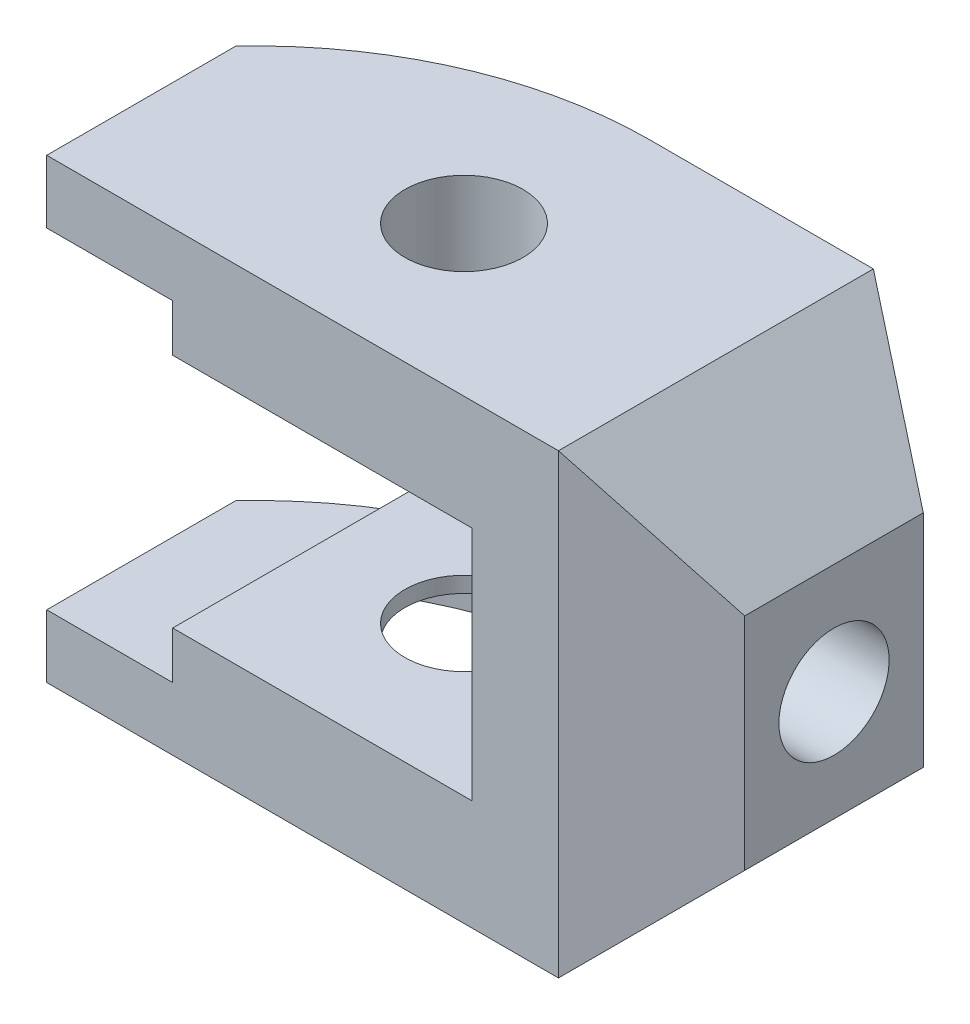
SolidWorks part; units mm, degrees
material "1060 Alloy"
ref_plane "Front Plane" through (0, 0, 0) normal (0, 0, 1) x (1, 0, 0)
ref_plane "Top Plane" through (0, 0, 0) normal (0, 1, 0) x (1, 0, 0)
ref_plane "Right Plane" through (0, 0, 0) normal (1, 0, 0) x (0, 0, -1)
sketch "Sketch1" plane through (0, 0, 0) normal (0, 1, 0) x (1, 0, 0)
  line L0 (0, 0) -> (65, 0)
  line L1 (0, 0) -> (0, 24)
  line L2 (65, 0) -> (80, 8.6603)
  line L3 (80, 8.6603) -> (80, 31.3397)
  line L4 (80, 31.3397) -> (65, 40)
  line L5 (65, 40) -> (36.6606, 40)
  arc A0 (0, 24) -> (36.6606, 40) centre (36.6606, -10) cw
  circle A1 centre (34, 19) radius 7.5
  dimension "D8" = 50
  dimension "D11" = 15
  dimension "D1" = 24
  dimension "D2" = 65
  dimension "D3" = 15
  dimension "D4" = 30
  dimension "D5" = 30
  dimension "D6" = 15
  dimension "D7" = 40
  dimension "D9" = 19
  dimension "D10" = 31
extrude "Boss-Extrude1" add sketch "Sketch1" along normal blind 58
sketch "Sketch2" plane through (0, 0, 0) normal (0, 0, 1) x (1, 0, 0)
  line L0 (0, 58) -> (0, 0) construction
  line L1 (0, 50) -> (16, 50)
  line L2 (0, 50) -> (0, 8)
  line L3 (0, 8) -> (16, 8)
  line L4 (16, 50) -> (16, 8)
  line L5 (0, 58) -> (65, 58) construction
  line L6 (16, 44) -> (54, 44)
  line L7 (54, 44) -> (54, 14)
  line L8 (54, 14) -> (16, 14)
  line L9 (0, 0) -> (65, 0) construction
  line L10 (65, 58) -> (65, 0) construction
  dimension "D1" = 8
  dimension "D2" = 16
  dimension "D3" = 14
  dimension "D4" = 14
  dimension "D5" = 11
  dimension "D6" = 8
extrude "Cut-Extrude1" cut sketch "Sketch2" against normal blind 58 contours L8 L7 L6 L4 | L4 L1 L2 L3
sketch "Sketch3" plane through (0, 0, 0) normal (0, 0, 1) x (1, 0, 0)
  line L9 (65, 58) -> (80, 58)
  line L10 (80, 58) -> (80, 43)
  line L11 (80, 58) -> (80, 0) construction
  line L12 (80, 43) -> (65, 58)
  line L13 (65, 0) -> (80, 0)
  line L14 (80, 0) -> (80, 15)
  line L15 (80, 15) -> (65, 0)
  point P9 (65.2292, 58)
  dimension "D1" = 45
  dimension "D2" = 45
extrude "Cut-Extrude2" cut sketch "Sketch3" against normal blind 58
sketch "Sketch4" plane through (0, 0, 0) normal (1, 0, 0) x (0, 0, -1)
  line L0 (40, 58) -> (40, 0) construction
  circle A0 centre (20, 29) radius 7
  dimension "D3" = 14
  dimension "D1" = 29
  dimension "D2" = 20
extrude "Cut-Extrude3" cut sketch "Sketch4" along normal blind 108
sketch "Sketch5" plane through (0, 0, 0) normal (0, 1, 0) x (1, 0, 0)
  line L8 (0, 24) -> (0, 0) construction
  line L9 (0, 20.9839) -> (0, 2)
  line L12 (2, 2) -> (63, 2)
  line L13 (63, 2) -> (63, 38)
  line L14 (63, 38) -> (36.6606, 38)
  line L15 (2, 23.2061) -> (2, 2)
  line L16 (0, 2) -> (63, 2)
  line L17 (63, 2) -> (63, 38)
  line L18 (63, 38) -> (36.6606, 38)
  arc A3 (36.6606, 38) -> (2, 23.2061) centre (36.6606, -10) ccw
  arc A4 (36.6606, 38) -> (0, 20.9839) centre (36.6606, -10) ccw
  dimension "D1" = 2
extrude "Cut-Extrude4" cut sketch "Sketch5" along normal blind 6
sketch "Sketch7" plane through (0, 0, 0) normal (0, 1, 0) x (1, 0, 0)
  line L4 (18, 32.045) -> (18, 4)
  line L5 (0, 20.9839) -> (0, 2) construction
  line L8 (2, 4) -> (61, 4)
  line L9 (2, 20.2431) -> (2, 4)
  line L10 (61, 36) -> (36.6606, 36)
  line L11 (61, 4) -> (61, 36)
  line L12 (18, 4) -> (61, 4)
  line L14 (61, 36) -> (36.6606, 36)
  line L15 (61, 4) -> (61, 36)
  arc A2 (36.6606, 36) -> (2, 20.2431) centre (36.6606, -10) ccw
  arc A3 (36.6606, 36) -> (18, 32.045) centre (36.6606, -10) ccw
  point P0 (18, 4.1176)
  point P4 (18, 4)
  point P6 (18, 32.0391)
  point P9 (0, 0)
  point P10 (0, 0)
  point P11 (17.9867, 31.5283)
  dimension "D2" = 18
  dimension "D1" = 2
extrude "Cut-Extrude5" cut sketch "Sketch7" along normal blind 12
